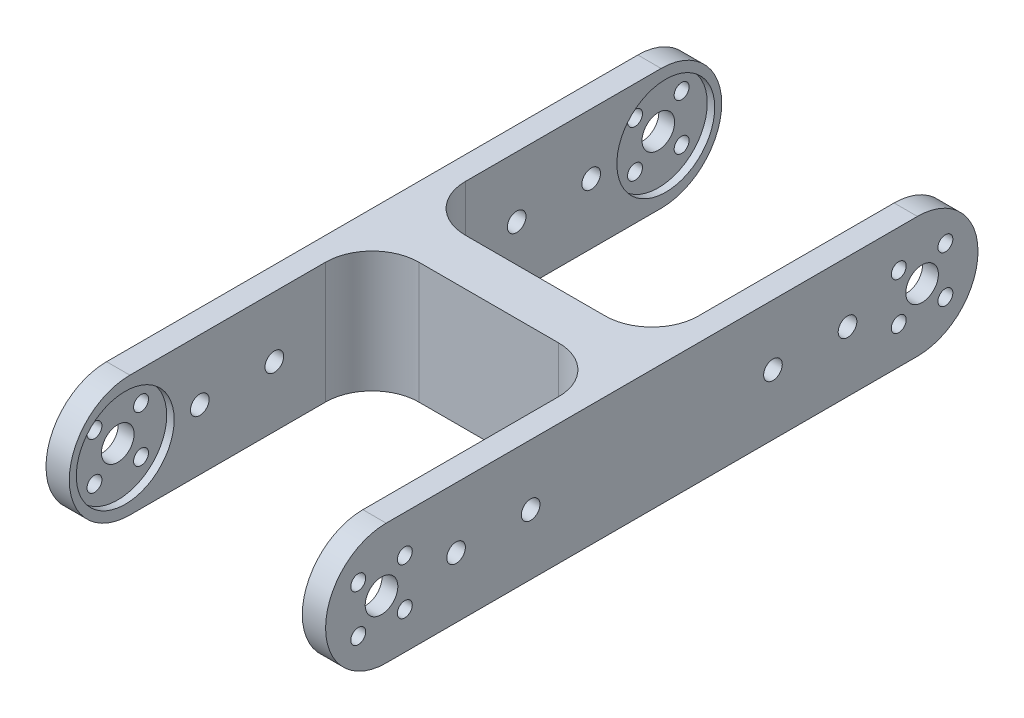
SolidWorks part; units mm, degrees
ref_plane "前视基准面" through (0, 0, 0) normal (0, 0, 1) x (1, 0, 0)
ref_plane "上视基准面" through (0, 0, 0) normal (0, 1, 0) x (1, 0, 0)
ref_plane "右视基准面" through (0, 0, 0) normal (1, 0, 0) x (0, 0, -1)
other "Configuration Table"
sketch "草图1" plane through (0, 0, 0) normal (0, 1, 0) x (1, 0, 0)
  line L0 (0, 0) -> (0, 140)
  line L1 (0, 140) -> (5, 140)
  line L2 (5, 140) -> (5, 85)
  line L3 (15, 75) -> (45, 75)
  line L4 (55, 85) -> (55, 140)
  line L5 (55, 140) -> (60, 140)
  line L6 (60, 140) -> (60, 0)
  line L7 (60, 0) -> (55, 0)
  line L8 (55, 0) -> (55, 55)
  line L9 (45, 65) -> (15, 65)
  line L10 (5, 55) -> (5, 0)
  line L11 (5, 0) -> (0, 0)
  arc A0 (55, 55) -> (45, 65) centre (45, 55) ccw
  arc A1 (5, 55) -> (15, 65) centre (15, 55) cw
  arc A2 (45, 75) -> (55, 85) centre (45, 85) ccw
  arc A3 (15, 75) -> (5, 85) centre (15, 85) cw
  point P3 (2.5, 140)
  point P16 (55, 65)
  point P19 (5, 65)
  point P22 (55, 75)
  point P25 (5, 75)
  dimension "D10" = 10
  dimension "D1" = 140
  dimension "D2" = 140
  dimension "D3" = 5
  dimension "D4" = 5
  dimension "D5" = 50
  dimension "D6" = 50
  dimension "D7" = 5
  dimension "D8" = 10
  dimension "D9" = 65
extrude "凸台-拉伸1" add sketch "草图1" along normal blind 26
sketch "草图2" plane through (60, 0, 0) normal (1, 0, 0) x (0, 0, -1)
  line L0 (-1000, 13) -> (49000, 13) construction
  line L1 (0, 26) -> (0, 0) construction
  line L2 (70, -974) -> (70, 49026) construction
  line L3 (0, 26) -> (140, 26) construction
  line L4 (0, 13) -> (12, 13)
  line L5 (12, 13) -> (28, 13)
  line L6 (7, 8) -> (17, 8)
  line L7 (7, 8) -> (7, 18)
  line L8 (7, 18) -> (17, 18)
  line L9 (17, 8) -> (17, 18)
  line L10 (7, 8) -> (17, 18) construction
  line L11 (7, 18) -> (17, 8) construction
  line L12 (28, 13) -> (44, 13)
  circle A0 centre (12, 13) radius 3.5
  circle A1 centre (7, 18) radius 1.6
  circle A2 centre (17, 18) radius 1.6
  circle A3 centre (17, 8) radius 1.6
  circle A4 centre (7, 8) radius 1.6
  circle A5 centre (28, 13) radius 2
  circle A6 centre (44, 13) radius 2
  circle A7 centre (96, 13) radius 2
  circle A8 centre (112, 13) radius 2
  circle A9 centre (123, 18) radius 1.6
  circle A10 centre (133, 18) radius 1.6
  circle A11 centre (133, 8) radius 1.6
  circle A12 centre (128, 13) radius 3.5
  circle A13 centre (123, 8) radius 1.6
  point P5 (0, 13)
  point P10 (70, 26)
  dimension "D2" = 7
  dimension "D5" = 3.2
  dimension "D8" = 4
  dimension "D10" = 4
  dimension "D1" = 12
  dimension "D3" = 10
  dimension "D4" = 10
  dimension "D7" = 16
  dimension "D9" = 16
  dimension "D6" = 4
extrude "切除-拉伸2" cut sketch "草图2" against normal through all contours A12 | A9 | A10 | A11 | A13 | A0 | A1 | A4 | A3 | A2 | A5 | A6 | A7 | A8
sketch "草图3" plane through (0, 0, 0) normal (-1, 0, 0) x (0, 0, 1)
  line L0 (-128, 13) -> (-127, 13)
  line L1 (-70, -974) -> (-70, 49026) construction
  line L2 (-140, 26) -> (-127, 26)
  line L3 (-140, 26) -> (-140, 0)
  line L4 (-140, 0) -> (-127, 0)
  line L5 (-127, 26) -> (-127, 0)
  line L6 (-140, 26) -> (0, 26) construction
  line L7 (0, 26) -> (-13, 26)
  line L8 (0, 26) -> (0, 0)
  line L9 (0, 0) -> (-13, 0)
  line L10 (-13, 26) -> (-13, 0)
  circle A2 centre (-127, 13) radius 13
  circle A3 centre (-13, 13) radius 13
  point P14 (-70, 26)
  line M8 (-140, 0) -> (0, 0)
  line M9 (0, 0) -> (0, 26)
  line M10 (0, 26) -> (-140, 26)
  line M11 (-140, 26) -> (-140, 0)
  dimension "D1" = 1
extrude "切除-拉伸5" cut sketch "草图3" against normal through all contours A2 M10 M11 | A2 L3 M8 | A3 M9 M8 | A3 L8 M10
sketch "草图5" plane through (55, 0, 0) normal (-1, 0, 0) x (0, 0, 1)
  circle A0 centre (-128, 13) radius 10.5
  dimension "D1" = 21
extrude "切除-拉伸6" cut sketch "草图5" against normal blind 1.6
sketch "草图6" plane through (5, 0, 0) normal (1, 0, 0) x (0, 0, -1)
  circle A0 centre (128, 13) radius 10.5
  dimension "D1" = 21
extrude "切除-拉伸7" cut sketch "草图6" against normal blind 1.6
sketch "草图7" plane through (55, 0, 0) normal (-1, 0, 0) x (0, 0, 1)
  circle A0 centre (-12, 13) radius 10.5
  dimension "D1" = 21
extrude "切除-拉伸8" cut sketch "草图7" against normal blind 1.6
sketch "草图8" plane through (5, 0, 0) normal (1, 0, 0) x (0, 0, -1)
  circle A0 centre (12, 13) radius 10.5
  dimension "D1" = 21
extrude "切除-拉伸9" cut sketch "草图8" against normal blind 1.6
sketch "草图9" plane through (0, 26, 0) normal (0, 1, 0) x (1, 0, 0)
  line L0 (30, -925) -> (30, 49075) construction
  line L1 (45, 75) -> (15, 75) construction
  line L2 (30, 75) -> (30, 65)
  line L3 (15, 65) -> (45, 65) construction
  point P5 (30, 75)
